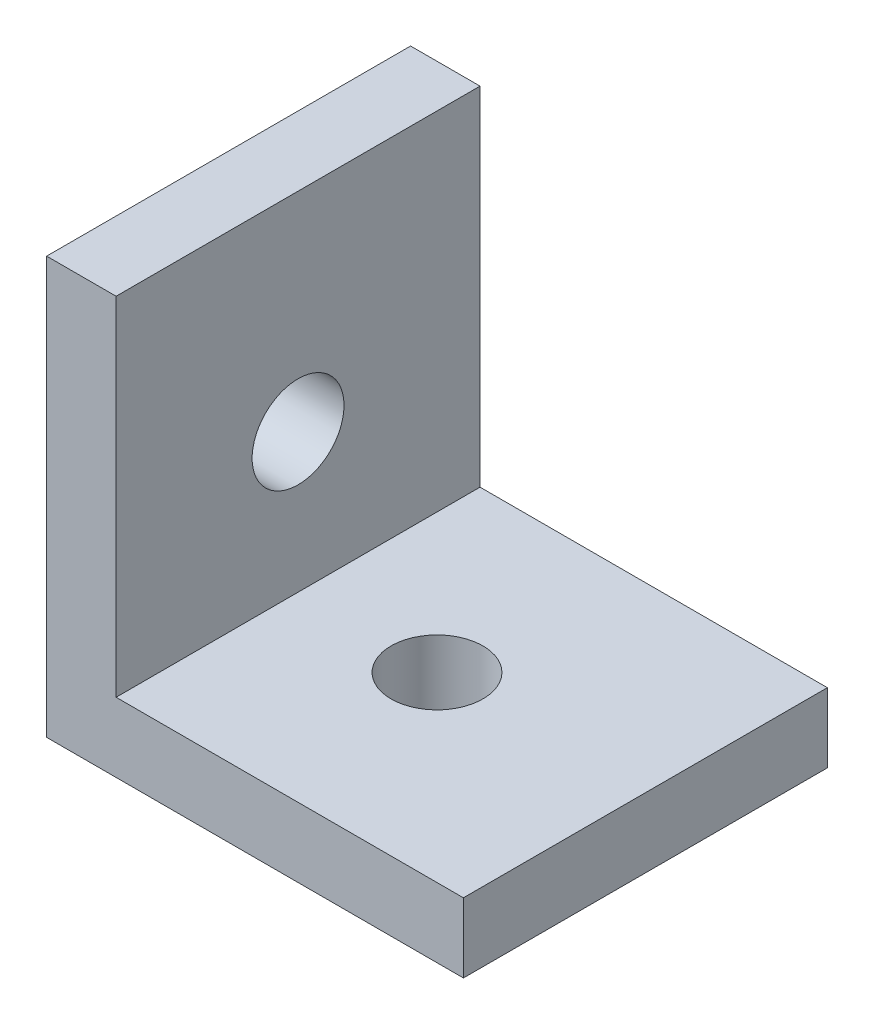
SolidWorks part; units mm, degrees
ref_plane "Front Plane" through (0, 0, 0) normal (0, 0, 1) x (1, 0, 0)
ref_plane "Top Plane" through (0, 0, 0) normal (0, 1, 0) x (1, 0, 0)
ref_plane "Right Plane" through (0, 0, 0) normal (1, 0, 0) x (0, 0, -1)
ref_plane "Plane_zm16_635" through (0, 0, -16.635) normal (0, 0, 1) x (1, 0, 0)
sketch "Sketch1" plane through (0, 0, -16.635) normal (0, 0, 1) x (1, 0, 0)
  line L0 (0, 0) -> (38.1, 0)
  line L1 (38.1, 0) -> (38.1, 6.35)
  line L2 (38.1, 6.35) -> (6.35, 6.35)
  line L3 (6.35, 6.35) -> (6.35, 38.1)
  line L4 (6.35, 38.1) -> (0, 38.1)
  line L5 (0, 38.1) -> (0, 0)
extrude "Body" add sketch "Sketch1" along normal blind 33.27
ref_plane "Plane_y6_35" through (0, 6.35, 0) normal (0, 1, 0) x (1, 0, 0)
sketch "Sketch2" plane through (0, 6.35, 0) normal (0, 1, 0) x (1, 0, 0)
  circle A0 centre (19.05, 0) radius 4.2
extrude "HolesX" cut sketch "Sketch2" against normal blind 6.35
ref_plane "Plane_x6_35" through (6.35, 0, 0) normal (1, 0, 0) x (0, 0, -1)
sketch "Sketch3" plane through (6.35, 0, 0) normal (1, 0, 0) x (0, 0, -1)
  circle A0 centre (0, 19.05) radius 4.2
extrude "HolesY" cut sketch "Sketch3" against normal blind 6.35
